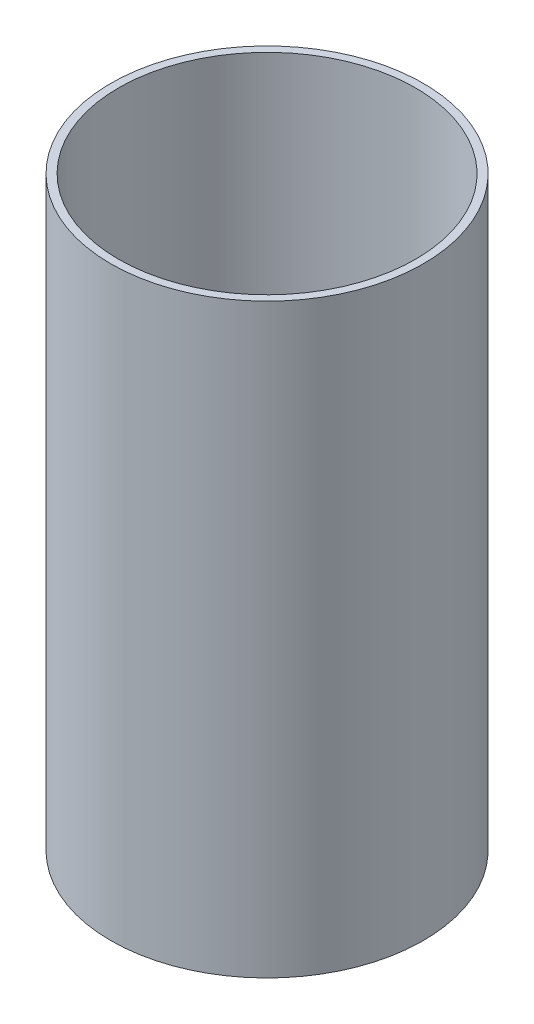
SolidWorks part; units mm, degrees
ref_plane "Front Plane" through (0, 0, 0) normal (0, 0, 1) x (1, 0, 0)
ref_plane "Top Plane" through (0, 0, 0) normal (0, 1, 0) x (1, 0, 0)
ref_plane "Right Plane" through (0, 0, 0) normal (1, 0, 0) x (0, 0, -1)
sketch "Sketch1" plane through (0, 0, 0) normal (0, 1, 0) x (1, 0, 0)
  circle A0 centre (0, 0) radius 40
  circle A1 centre (0, 0) radius 38
  dimension "D1" = 80
  dimension "D2" = 2
extrude "Boss-Extrude1" add sketch "Sketch1" along normal blind 150
